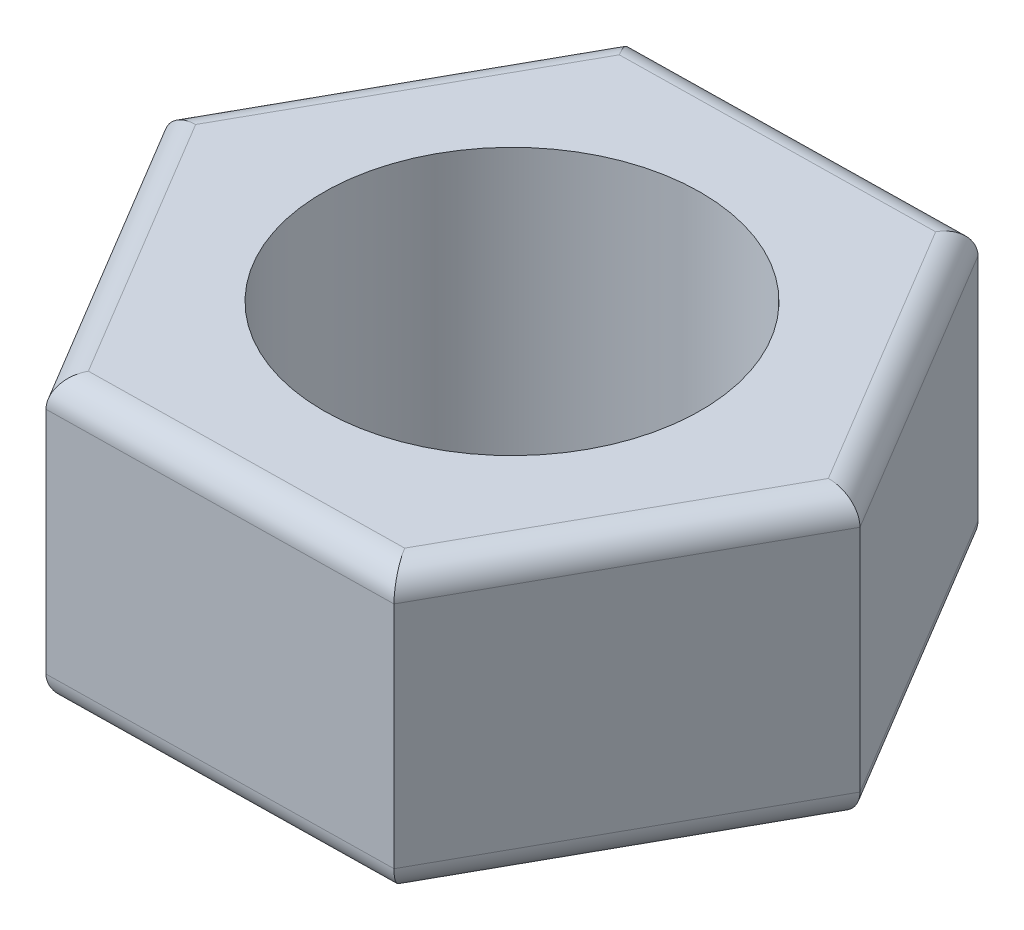
SolidWorks part; units mm, degrees
ref_plane "Спереди" through (0, 0, 0) normal (0, 0, 1) x (1, 0, 0)
ref_plane "Сверху" through (0, 0, 0) normal (0, 1, 0) x (1, 0, 0)
ref_plane "Справа" through (0, 0, 0) normal (1, 0, 0) x (0, 0, -1)
sketch "Эскиз1" plane through (0, 0, 0) normal (0, 1, 0) x (1, 0, 0)
  line L1 (6.5237, -10.8984) -> (12.7001, 0.2005)
  line L2 (12.7001, 0.2005) -> (6.1764, 11.0989)
  line L3 (6.1764, 11.0989) -> (-6.5237, 10.8984)
  line L4 (-6.5237, 10.8984) -> (-12.7001, -0.2005)
  line L5 (-12.7001, -0.2005) -> (-6.1764, -11.0989)
  line L6 (-6.1764, -11.0989) -> (6.5237, -10.8984)
  circle A0 centre (0, 0) radius 11 construction
  circle A1 centre (0, 0) radius 7
  dimension "D1" = 22
extrude "Вытянуть1" add sketch "Эскиз1" along normal blind 10.5
fillet "Скругление1" radius 1 12 edges at (-9.4383, 0, 5.6497) (-9.6119, 0, -5.349) (-0.1736, 0, -10.9986) (9.4383, 0, -5.6497) (9.6119, 0, 5.349) (0.1736, 0, 10.9986) (-9.4383, 10.5, 5.6497) (-9.6119, 10.5, -5.349) (-0.1736, 10.5, -10.9986) (9.4383, 10.5, -5.6497) (9.6119, 10.5, 5.349) (0.1736, 10.5, 10.9986)
